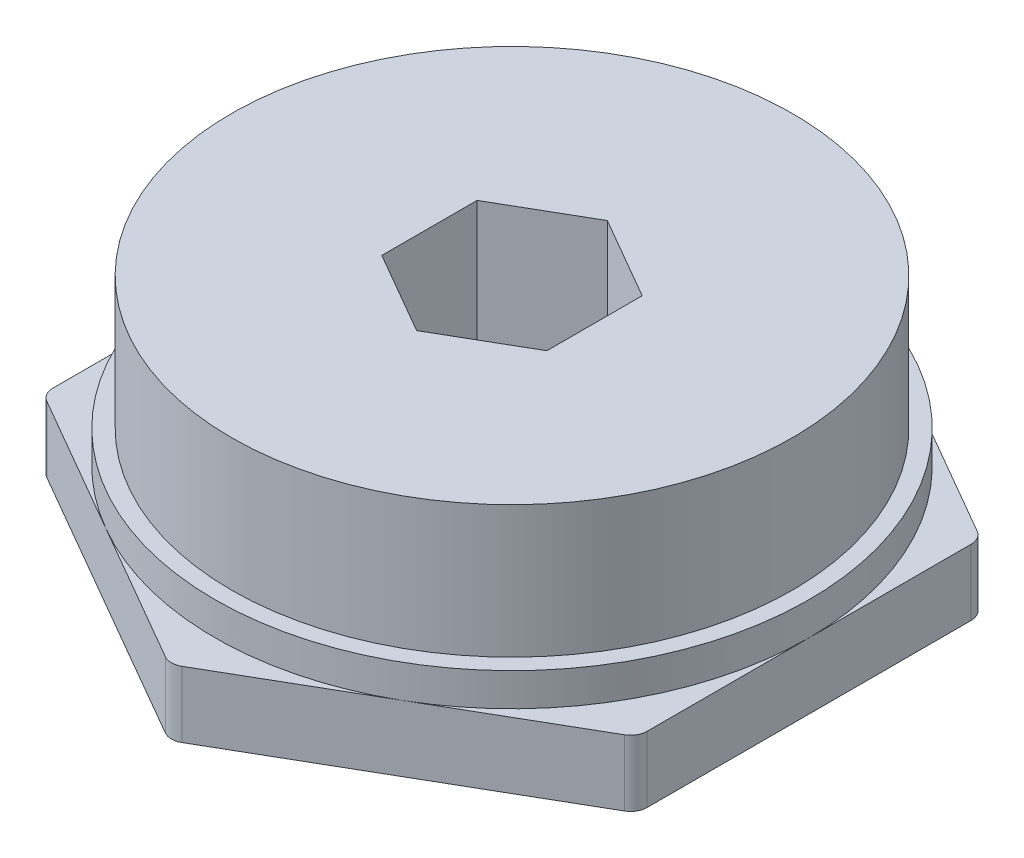
SolidWorks part; units mm, degrees
material "ABS"
ref_plane "Front Plane" through (0, 0, 0) normal (0, 0, 1) x (1, 0, 0)
ref_plane "Top Plane" through (0, 0, 0) normal (0, 1, 0) x (1, 0, 0)
ref_plane "Right Plane" through (0, 0, 0) normal (1, 0, 0) x (0, 0, -1)
ref_plane "Plane2" through (0, 31, 0) normal (0, 1, 0) x (1, 0, 0)
sketch "Sketch1" plane through (0, 31, 0) normal (0, 1, 0) x (1, 0, 0)
  line L1 (0, 10.3923) -> (-9, 5.1962)
  line L2 (-9, 5.1962) -> (-9, -5.1962)
  line L3 (-9, -5.1962) -> (0, -10.3923)
  line L4 (0, -10.3923) -> (9, -5.1962)
  line L5 (9, -5.1962) -> (9, 5.1962)
  line L6 (9, 5.1962) -> (0, 10.3923)
  circle A0 centre (0, 0) radius 9 construction
  dimension "D1" = 18
extrude "Boss-Extrude1" add sketch "Sketch1" along normal blind 2
fillet "Fillet1" radius 0.5 6 edges at (0, 32, -10.3923) (-9, 32, -5.1962) (-9, 32, 5.1962) (0, 32, 10.3923) (9, 32, 5.1962) (9, 32, -5.1962)
sketch "Sketch2" plane through (0, 33, 0) normal (0, 1, 0) x (1, 0, 0)
  circle A1 centre (0, 0) radius 9
  dimension "D2" = 18
extrude "Boss-Extrude2" add sketch "Sketch2" along normal blind 1 contours A1
sketch "Sketch3" plane through (0, 34, 0) normal (0, 1, 0) x (1, 0, 0)
  circle A0 centre (0, 0) radius 8.5
  dimension "D1" = 17
extrude "Boss-Extrude3" add sketch "Sketch3" along normal blind 4
sketch "Sketch4" plane through (0, 38, 0) normal (0, 1, 0) x (1, 0, 0)
  line L1 (0, 2.8868) -> (-2.5, 1.4434)
  line L2 (-2.5, 1.4434) -> (-2.5, -1.4434)
  line L3 (-2.5, -1.4434) -> (0, -2.8868)
  line L4 (0, -2.8868) -> (2.5, -1.4434)
  line L5 (2.5, -1.4434) -> (2.5, 1.4434)
  line L6 (2.5, 1.4434) -> (0, 2.8868)
  circle A0 centre (0, 0) radius 2.5 construction
  dimension "D1" = 5
extrude "Cut-Extrude1" cut sketch "Sketch4" against normal through all
